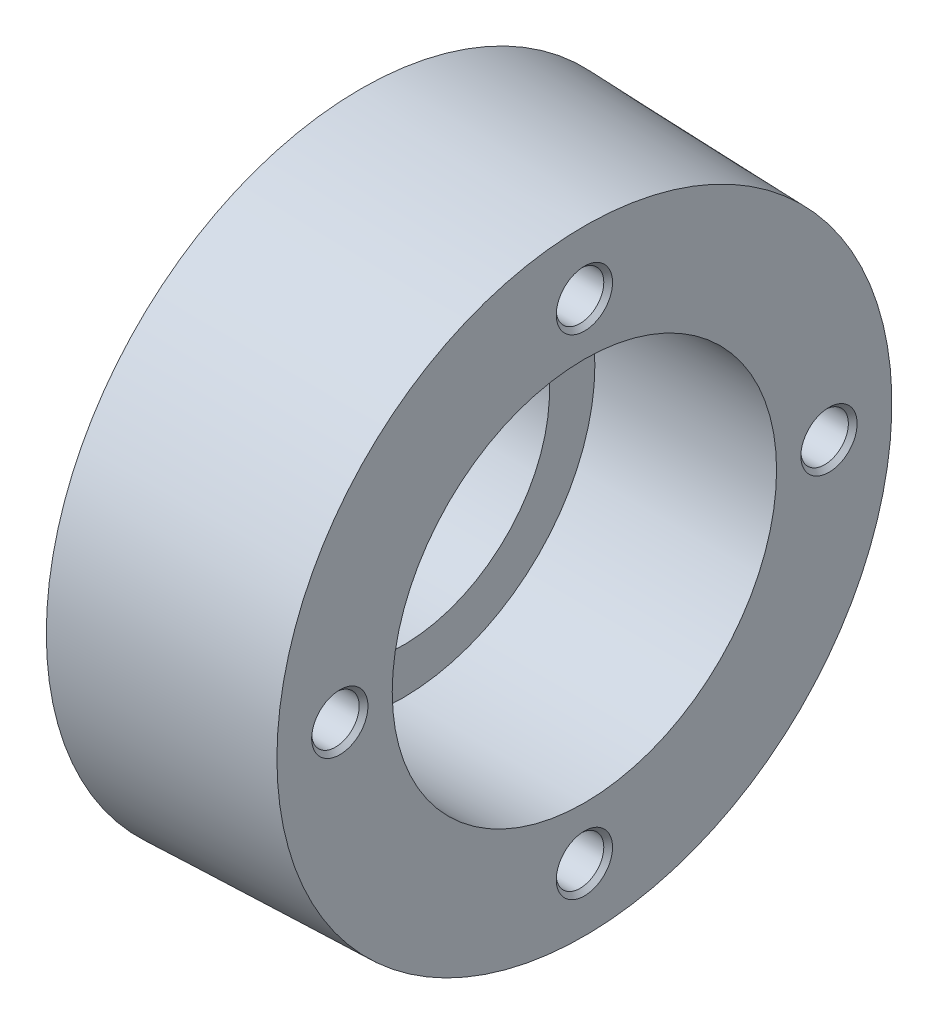
SolidWorks part; units mm, degrees
ref_plane "Ön Düzlem" through (0, 0, 0) normal (0, 0, 1) x (1, 0, 0)
ref_plane "Üst Düzlem" through (0, 0, 0) normal (0, 1, 0) x (1, 0, 0)
ref_plane "Sağ Düzlem" through (0, 0, 0) normal (1, 0, 0) x (0, 0, -1)
sketch "Sketch1" plane through (0, 0, 0) normal (0, 0, 1) x (1, 0, 0)
  line L0 (0, 0) -> (25.5812, 0) construction
  line L1 (0, 21) -> (11, 21)
  line L2 (0, 21) -> (0, 28)
  line L3 (0, 28) -> (5, 28)
  line L4 (5, 28) -> (5, 45)
  line L5 (5, 45) -> (37, 44)
  line L6 (37, 44) -> (37, 27.5)
  line L7 (37, 27.5) -> (11, 27.5)
  line L8 (11, 27.5) -> (11, 21)
  dimension "D1" = 27.5
  dimension "D2" = 28
  dimension "D3" = 21
  dimension "D4" = 5
  dimension "D5" = 45
  dimension "D6" = 44
  dimension "D7" = 37
  dimension "D8" = 26
revolve "Revolve1" add sketch "Sketch1" angle 360 about L0
hole_wizard "M8 Tapped Hole1" positions "Sketch2" profile "Sketch4" tap size "M8" standard "ISO"
sketch "Sketch2" plane through (37, 0, 0) normal (1, 0, 0) x (0, 0, -1)
  point P0 (0, 35)
  dimension "D1" = 35
sketch "Sketch4" plane through (37, 35, 0) normal (0, 1, 0) x (0, 0, -1)
  line L0 (0, 0) -> (0, 24.2929)
  line L1 (0, 24.2929) -> (3.4, 22.25)
  line L2 (3.4, 22.25) -> (3.4, 0.625)
  line L3 (3.4, 0.625) -> (4.025, 0)
  line L5 (4.025, 0) -> (0, 0)
  line L6 (-3.4, 0.625) -> (-4.025, 0) construction
  line L10 (0, 24.2929) -> (-3.4, 22.25) construction
  line L11 (0, -6.35) -> (0, 107.95) construction
  dimension "Tap Drill Dia." = 6.8
  dimension "Tap Drill Depth" = 22.25
  dimension "Near C'Sink Dia." = 8.05
  dimension "Near C'Sink Angle" = 90
  dimension "Drill Angle" = 118
cosmetic thread "Hole Thread1" parameters "D1"=16, "D2"=8
pattern_circular "CirPattern1" count 4 over 360 about axis through (0, 0, 0) along (1, 0, 0) of "M8 Tapped Hole1"
cosmetic thread "Hole Thread2" parameters "D1"=16, "D2"=8
cosmetic thread "Hole Thread3" parameters "D1"=16, "D2"=8
cosmetic thread "Hole Thread4" parameters "D1"=16, "D2"=8
